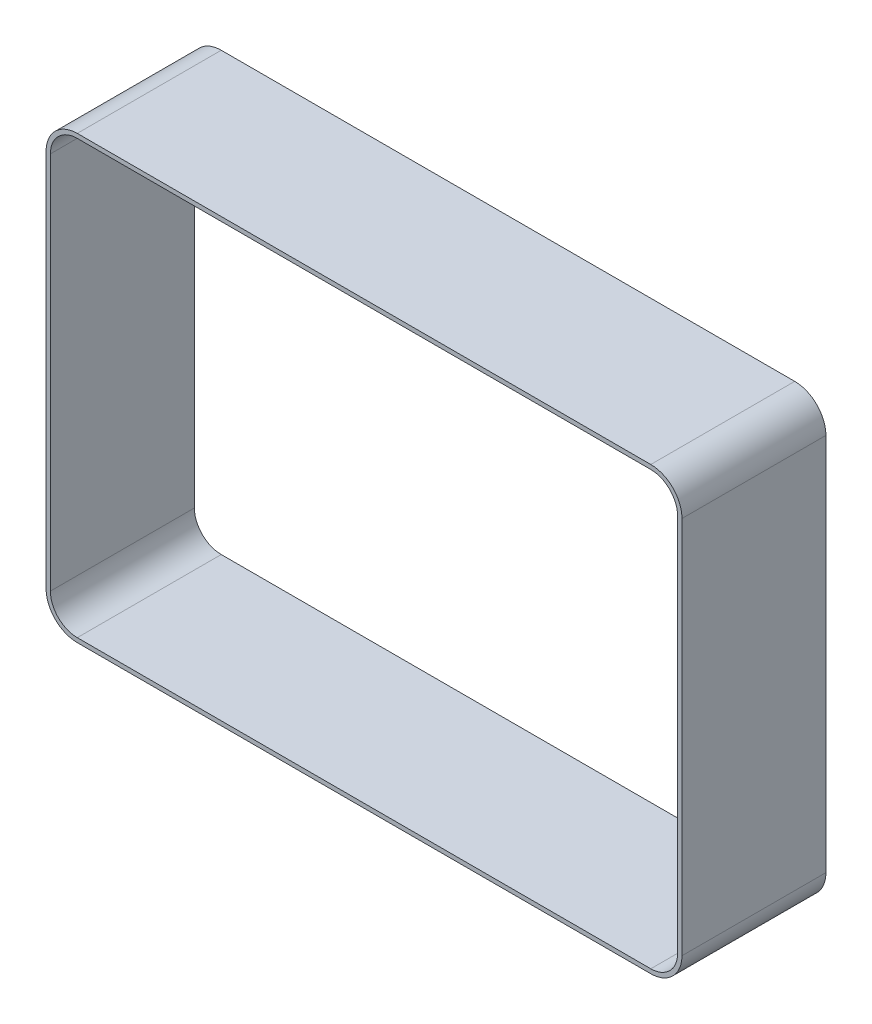
SolidWorks part; units mm, degrees
ref_plane "Front Plane" through (0, 0, 0) normal (0, 0, 1) x (1, 0, 0)
ref_plane "Top Plane" through (0, 0, 0) normal (0, 1, 0) x (1, 0, 0)
ref_plane "Right Plane" through (0, 0, 0) normal (1, 0, 0) x (0, 0, -1)
sketch "Sketch1" plane through (0, 0, 0) normal (0, 0, 1) x (1, 0, 0)
  line L1 (-151.765, -116.713) -> (151.765, -116.713)
  line L2 (-168.275, -100.203) -> (-168.275, 100.203)
  line L3 (-151.765, 116.713) -> (151.765, 116.713)
  line L4 (168.275, -100.203) -> (168.275, 100.203)
  line L5 (-151.765, -114.427) -> (151.765, -114.427)
  line L6 (-165.989, -100.203) -> (-165.989, 100.203)
  line L7 (-151.765, 114.427) -> (151.765, 114.427)
  line L8 (165.989, -100.203) -> (165.989, 100.203)
  arc A0 (-165.989, -100.203) -> (-151.765, -114.427) centre (-151.765, -100.203) ccw
  arc A1 (151.765, -114.427) -> (165.989, -100.203) centre (151.765, -100.203) ccw
  arc A2 (165.989, 100.203) -> (151.765, 114.427) centre (151.765, 100.203) ccw
  arc A3 (-151.765, 114.427) -> (-165.989, 100.203) centre (-151.765, 100.203) ccw
  arc A4 (-168.275, -100.203) -> (-151.765, -116.713) centre (-151.765, -100.203) ccw
  arc A5 (151.765, -116.713) -> (168.275, -100.203) centre (151.765, -100.203) ccw
  arc A6 (168.275, 100.203) -> (151.765, 116.713) centre (151.765, 100.203) ccw
  arc A7 (-151.765, 116.713) -> (-168.275, 100.203) centre (-151.765, 100.203) ccw
  dimension "D1" = 14.224
  dimension "D2" = 16.51
extrude "Boss-Extrude4" add sketch "Sketch1" along normal blind 76.2
